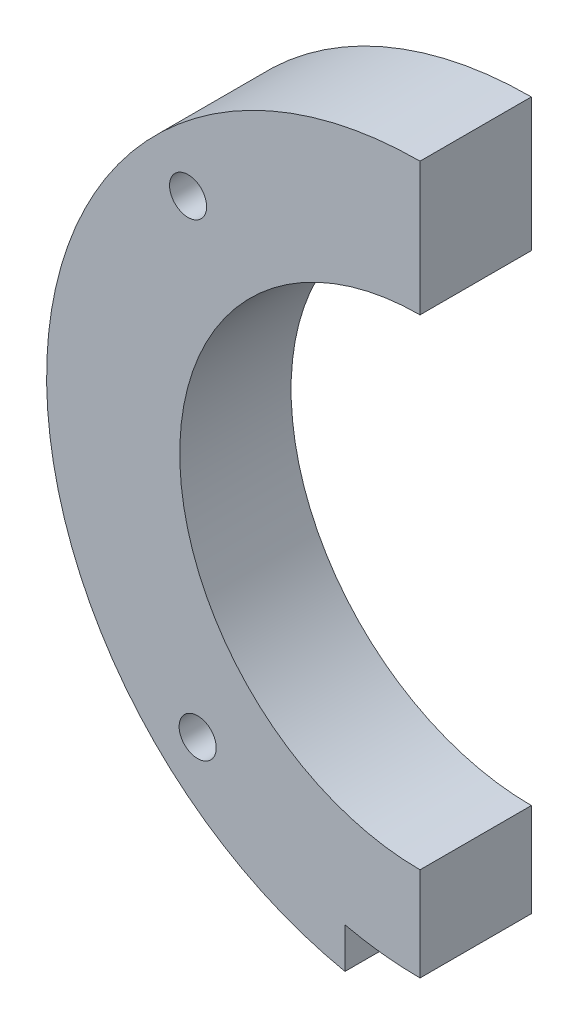
SolidWorks part; units mm, degrees
material "Pine"
ref_plane "Front Plane" through (0, 0, 0) normal (0, 0, 1) x (1, 0, 0)
ref_plane "Top Plane" through (0, 0, 0) normal (0, 1, 0) x (1, 0, 0)
ref_plane "Right Plane" through (0, 0, 0) normal (1, 0, 0) x (0, 0, -1)
sketch "Sketch1" plane through (0, 0, 0) normal (0, 0, 1) x (1, 0, 0)
  line L5 (27, 10.6484) -> (27, 15)
  line L9 (35.0863, 14.0801) -> (35.0863, 90.3323) construction
  line L11 (35.0863, 90.3323) -> (35.0863, 75.9801)
  line L12 (35.0863, 24.1801) -> (35.0863, 14.0801)
  arc A3 (35.0863, 75.9801) -> (35.0863, 24.1801) centre (35.0863, 50.0801) ccw
  arc A4 (35.0863, 90.3323) -> (27, 10.6484) centre (35.0863, 50.0801) ccw
  arc A5 (27, 15) -> (35.0863, 14.0801) centre (35.0863, 50.0801) ccw
  point P6 (-5, 46.4286)
  point P8 (27, -5)
  dimension "D2" = 51.8
  dimension "D3" = 35.0863
  dimension "D7" = 40.2522
  dimension "D4" = 36
  dimension "D5" = 4.3516
  dimension "D1" = 50.0801
extrude "Boss-Extrude1" add sketch "Sketch1" along normal blind 12
sketch "Sketch2" plane through (0, 0, 12) normal (0, 0, 1) x (1, 0, 0)
  line L1 (35.0863, 75.9801) -> (35.0863, 90.3323) construction
  circle A0 centre (10.0863, 74.575) radius 2
  circle A1 centre (11.1178, 24.575) radius 2
  arc A4 (31.8341, 84.9287) -> (19.6109, 18.6872) centre (35.0863, 50.0801) ccw construction
  dimension "D1" = 35
  dimension "D2" = 4
  dimension "D3" = 50
  dimension "D4" = 25
extrude "Cut-Extrude1" cut sketch "Sketch2" against normal blind 20
